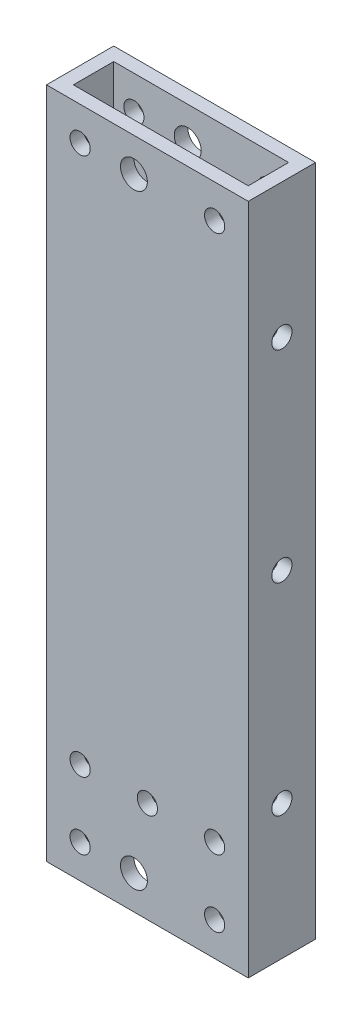
SolidWorks part; units mm, degrees
ref_plane "前视基准面" through (0, 0, 0) normal (0, 0, 1) x (1, 0, 0)
ref_plane "上视基准面" through (0, 0, 0) normal (0, 1, 0) x (1, 0, 0)
ref_plane "右视基准面" through (0, 0, 0) normal (1, 0, 0) x (0, 0, -1)
sketch "草图1" plane through (0, 0, 0) normal (0, 1, 0) x (1, 0, 0)
  line L1 (-15, 5) -> (15, 5)
  line L2 (-15, 5) -> (-15, -5)
  line L3 (-15, -5) -> (15, -5)
  line L4 (15, 5) -> (15, -5)
  line L5 (-15, 5) -> (15, -5) construction
  line L6 (-15, -5) -> (15, 5) construction
  line L7 (-13, 3) -> (13, 3)
  line L8 (-13, 3) -> (-13, -3)
  line L9 (-13, -3) -> (13, -3)
  line L10 (13, 3) -> (13, -3)
  line L11 (-13, 3) -> (13, -3) construction
  line L12 (-13, -3) -> (13, 3) construction
  point P0 (0, 0)
  point P6 (0, 0)
  dimension "D1" = 30
  dimension "D2" = 10
  dimension "D3" = 2
  dimension "D4" = 2
extrude "凸台-拉伸1" add sketch "草图1" along normal mid plane 100
sketch "草图2" plane through (0, 0, -5) normal (0, 0, -1) x (-1, 0, 0)
  line L0 (15, 50) -> (15, -50) construction
  line L1 (10, 45) -> (-10, 45) construction
  line L2 (-15, 50) -> (-15, -50) construction
  line L3 (0, 0) -> (-102.1073, 0) construction
  circle A0 centre (2, 45) radius 2
  circle A1 centre (10, 45) radius 1.5
  circle A2 centre (-10, 45) radius 1.5
  circle A3 centre (-10, -45) radius 1.5
  circle A4 centre (2, -45) radius 2
  circle A5 centre (10, -45) radius 1.5
  dimension "D1" = 4
  dimension "D4" = 3
  dimension "D2" = 5
  dimension "D3" = 5
extrude "切除-拉伸1" cut sketch "草图2" against normal through all
sketch "草图3" plane through (0, 0, 5) normal (0, 0, 1) x (1, 0, 0)
  circle A0 centre (0, -35) radius 1.5
  circle A1 centre (10, -35) radius 1.5
  circle A2 centre (-10, -35) radius 1.5
extrude "切除-拉伸2" cut sketch "草图3" against normal through all
sketch "草图4" plane through (15, 0, 0) normal (1, 0, 0) x (0, 0, -1)
  circle A0 centre (0, 30) radius 1.5
  circle A1 centre (0, 0) radius 1.5
  circle A2 centre (0, -30) radius 1.5
  point P8 (2.3044, -29.9082)
  point P9 (0, -30)
  dimension "D1" = 3
extrude "切除-拉伸3" cut sketch "草图4" against normal through all
